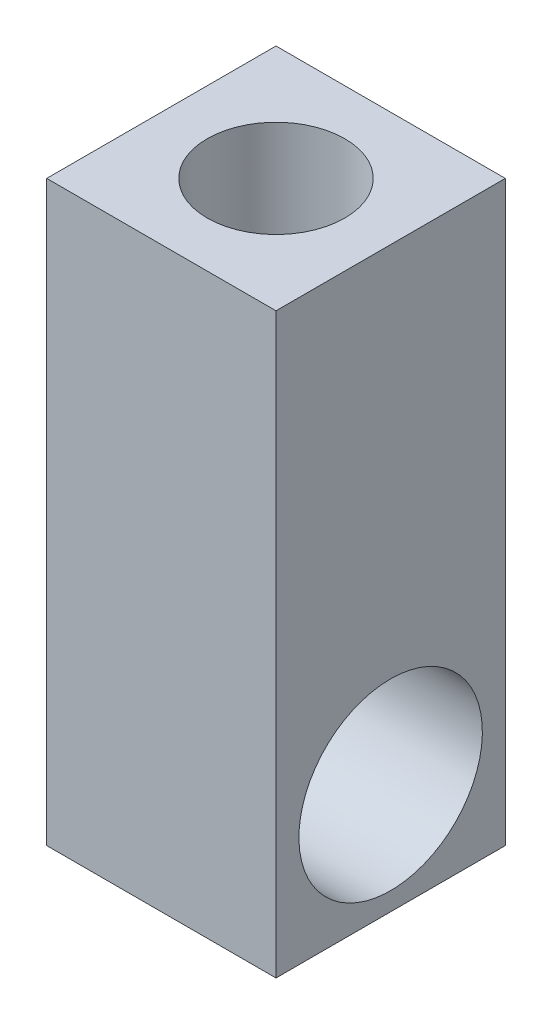
SolidWorks part; units mm, degrees
ref_plane "Front Plane" through (0, 0, 0) normal (0, 0, 1) x (1, 0, 0)
ref_plane "Top Plane" through (0, 0, 0) normal (0, 1, 0) x (1, 0, 0)
ref_plane "Right Plane" through (0, 0, 0) normal (1, 0, 0) x (0, 0, -1)
sketch "Sketch1" plane through (0, 0, 0) normal (0, 0, 1) x (1, 0, 0)
  line L1 (-1.25, 5) -> (1.25, 5)
  line L2 (-1.25, 5) -> (-1.25, -5)
  line L3 (-1.25, -5) -> (1.25, -5)
  line L4 (1.25, 5) -> (1.25, -5)
  line L5 (-1.25, 5) -> (1.25, -5) construction
  line L6 (-1.25, -5) -> (1.25, 5) construction
  point P0 (0, 0)
  dimension "D1" = 10
  dimension "D2" = 2.5
extrude "Boss-Extrude1" add sketch "Sketch1" along normal blind 2.5
sketch "Sketch2" plane through (0, 5, 0) normal (0, 1, 0) x (1, 0, 0)
  line L0 (0, 0) -> (0, -2.5) construction
  line L1 (1.25, -2.5) -> (-1.25, -2.5) construction
  line L2 (-1.25, -1.25) -> (1.25, -1.25) construction
  line L3 (-1.25, -2.5) -> (-1.25, 0) construction
  line L4 (1.25, -2.5) -> (1.25, 0) construction
  circle A0 centre (0, -1.25) radius 0.75
  dimension "D1" = 1.5
extrude "Cut-Extrude1" cut sketch "Sketch2" against normal blind 3
sketch "Sketch3" plane through (-1.25, 0, 0) normal (-1, 0, 0) x (0, 0, 1)
  line L0 (1.25, 5) -> (1.25, -5) construction
  line L1 (2.5, 5) -> (0, 5) construction
  line L2 (2.5, -5) -> (0, -5) construction
  line L3 (0, 0) -> (2.5, 0) construction
  line L4 (2.5, 5) -> (2.5, -5) construction
  line L5 (1.25, -4.8) -> (1.25, -5)
  circle A2 centre (1.25, -3.8) radius 1
  dimension "D1" = 2
  dimension "D2" = 0.2
extrude "Cut-Extrude3" cut sketch "Sketch3" against normal blind 7.5 contours A2
sketch "Sketch4" plane through (0, 5, 0) normal (0, 1, 0) x (1, 0, 0)
  line L0 (-1.25, -2.5) -> (-1.25, 0)
  line L5 (-1.25, 0) -> (1.25, 0)
  line L6 (1.25, 0) -> (1.25, -2.5)
  line L11 (1.25, -2.5) -> (-1.25, -2.5)
  point P0 (0, -1.2482)
extrude "Cut-Extrude5" cut sketch "Sketch4" against normal blind 2
sketch "Sketch6" plane through (0, 3, 0) normal (0, 1, 0) x (1, 0, 0)
  line L0 (-1.25, -1.25) -> (1.25, -1.25) construction
  line L1 (-1.25, 0) -> (-1.25, -2.5) construction
  line L2 (1.25, -2.5) -> (1.25, 0) construction
  line L3 (0, 0) -> (0, -2.5) construction
  line L4 (-1.25, -2.5) -> (1.25, -2.5) construction
  circle A0 centre (0, -1.25) radius 0.75
  dimension "D1" = 1.5
extrude "Cut-Extrude7" cut sketch "Sketch6" against normal blind 3
sketch "Sketch7" plane through (0, 3, 0) normal (0, 1, 0) x (1, 0, 0)
  line L0 (-1.25, 0) -> (1.25, 0)
  line L1 (1.25, 0) -> (1.25, -2.5)
  line L2 (1.25, -2.5) -> (-1.25, -2.5)
  line L3 (-1.25, -2.5) -> (-1.25, 0)
extrude "Cut-Extrude8" cut sketch "Sketch7" against normal blind 1
sketch "Sketch8" plane through (0, 0, 0) normal (0, 1, 0) x (1, 0, 0)
  circle A0 centre (0, -1.25) radius 0.75
extrude "Cut-Extrude9" cut sketch "Sketch8" against normal blind 2.5
sketch "Sketch9" plane through (-1.25, 0, 0) normal (-1, 0, 0) x (0, 0, 1)
  line L1 (0, -2.6) -> (2.5, -2.6)
  line L2 (0, -2.6) -> (0, -5)
  line L3 (0, -5) -> (2.5, -5)
  line L4 (2.5, -2.6) -> (2.5, -5)
  line L5 (0, -2.6) -> (2.5, -5) construction
  line L6 (0, -5) -> (2.5, -2.6) construction
  line L7 (0, -0.2) -> (2.5, -0.2)
  line L8 (0, -0.2) -> (0, -2.6)
  line L9 (0, -2.6) -> (2.5, -2.6)
  line L10 (2.5, -0.2) -> (2.5, -2.6)
  line L11 (0, -0.2) -> (2.5, -2.6) construction
  line L12 (0, -2.6) -> (2.5, -0.2) construction
  circle A1 centre (1.25, -1.4) radius 1
  point P0 (1.25, -3.8)
  point P5 (1.25, -1.4)
  circle M6 centre (1.25, -3.8) radius 1
  line M7 (2.5, -5) -> (2.5, 2)
  line M9 (0, 2) -> (0, -5)
  line M10 (0, -5) -> (2.5, -5)
  dimension "D3" = 2
  dimension "D1" = 2.4
  dimension "D2" = 2.5
extrude "Cut-Extrude11" cut sketch "Sketch9" against normal blind 10 contours L1 M9 M10 M7 M6 | A1
sketch "Sketch10" plane through (1.25, 0, 0) normal (1, 0, 0) x (0, 0, -1)
  line L9 (-2.5, -0.2) -> (0, -0.2)
  line L10 (-2.5, -0.2) -> (-2.5, -2.6)
  line L11 (-2.5, -2.6) -> (0, -2.6)
  line L12 (0, -0.2) -> (0, -2.6)
  line L13 (-2.5, -0.2) -> (0, -2.6) construction
  line L14 (-2.5, -2.6) -> (0, -0.2) construction
  line L15 (-2.5, -2.6) -> (0, -2.6)
  line L16 (-2.5, -2.6) -> (-2.5, -5)
  line L17 (-2.5, -5) -> (0, -5)
  line L18 (0, -2.6) -> (0, -5)
  circle A0 centre (-1.25, -1.4) radius 1
  point P0 (-1.25, -1.4)
  circle M4 centre (-1.25, -1.4) radius 1
  line M5 (-2.5, -2.6) -> (0, -2.6)
  dimension "D2" = 2
  dimension "D1" = 2.4
extrude "Boss-Extrude2" add sketch "Sketch10" against normal blind 2.5 contours M4 | L18 L16 L17 M5
sketch "Sketch11" plane through (1.25, 0, 0) normal (1, 0, 0) x (0, 0, -1)
  line L0 (-2.5, -5) -> (0, -5)
  line L2 (0, -5) -> (0, -2.6)
  circle A0 centre (-1.25, -3.8) radius 1
  dimension "D2" = 2
extrude "Cut-Extrude12" cut sketch "Sketch11" against normal blind 2.5 contours A0
sketch "Sketch12" plane through (-1.25, 0, 0) normal (-1, 0, 0) x (0, 0, 1)
  circle A0 centre (1.25, -3.8) radius 1
extrude "Boss-Extrude3" add sketch "Sketch12" against normal blind 2.5
sketch "Sketch13" plane through (1.25, 0, 0) normal (1, 0, 0) x (0, 0, -1)
  line L0 (-2.5, -5) -> (0, -5)
  line L5 (-2.5, -5) -> (-2.5, -4.3)
  line L6 (0, -5) -> (0, -4.3)
  line L7 (-2.5, -4.3) -> (0, -4.3)
  dimension "D1" = 0.7
extrude "Cut-Extrude13" cut sketch "Sketch13" against normal blind 2.5
sketch "Sketch14" plane through (1.25, 0, 0) normal (1, 0, 0) x (0, 0, -1)
  line L0 (-2.5, -4.3) -> (0, -4.3)
  line L2 (0, -4.3) -> (0, -1.9)
  line L4 (-2.5, -3.1) -> (0, -3.1) construction
  line L5 (-1.25, -1.9) -> (-1.25, -4.3) construction
  circle A0 centre (-1.25, -3.1) radius 1
  dimension "D2" = 2
extrude "Cut-Extrude14" cut sketch "Sketch14" against normal blind 2.5 contours A0
